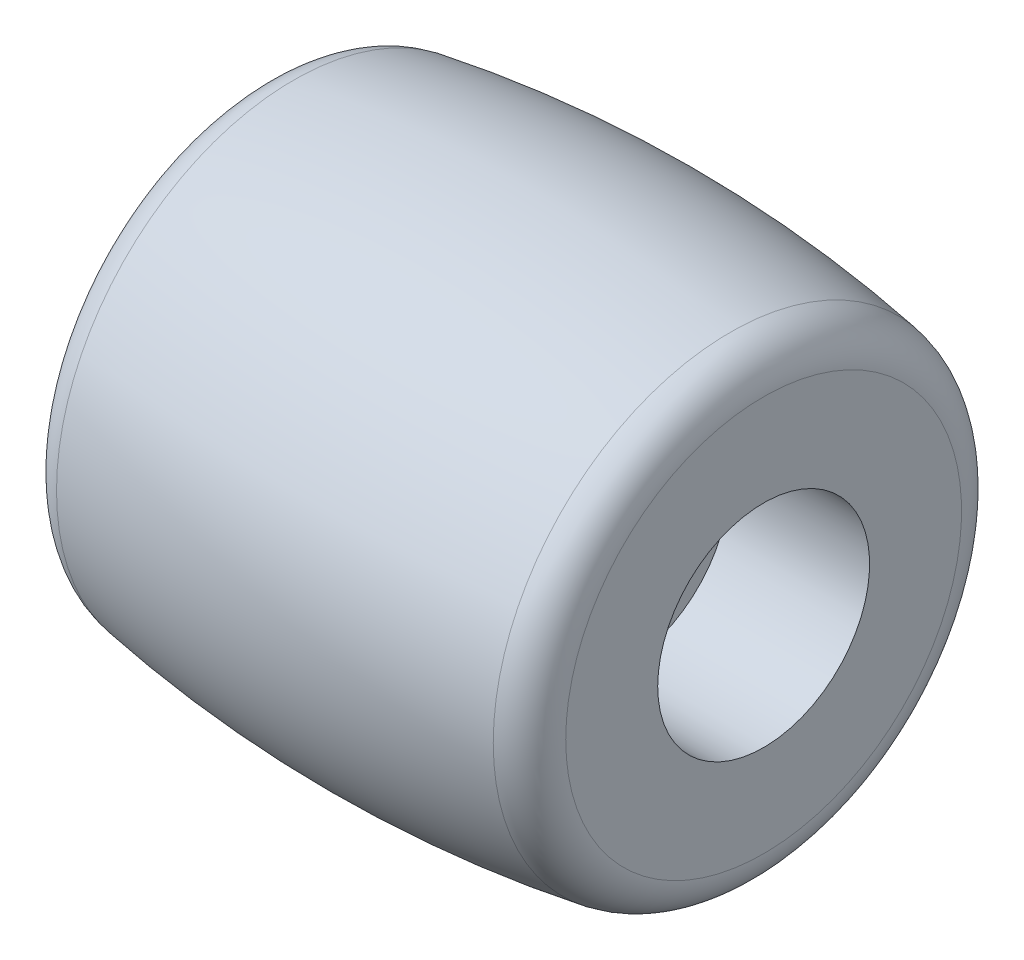
SolidWorks part; units mm, degrees
material "天然ｺﾞﾑ"
ref_plane "正面" through (0, 0, 0) normal (0, 0, 1) x (1, 0, 0)
ref_plane "平面" through (0, 0, 0) normal (0, 1, 0) x (1, 0, 0)
ref_plane "右側面" through (0, 0, 0) normal (1, 0, 0) x (0, 0, -1)
sketch "ｽｹｯﾁ1" plane through (0, 0, 0) normal (0, 0, 1) x (1, 0, 0)
  line L0 (0, 0) -> (12131.0927, 0) construction
  line L1 (4.2, 2.5) -> (-4.2, 2.5)
  line L2 (-4.2, 2.5) -> (-4.2, 4)
  line L3 (-4.2, 4) -> (-9.5, 4)
  line L4 (-9.5, 4) -> (-9.5, 8.7288)
  line L5 (4.2, 2.5) -> (4.2, 4)
  line L6 (4.2, 4) -> (9.5, 4)
  line L7 (9.5, 4) -> (9.5, 8.7288)
  line L8 (0, 0) -> (0, 9.625) construction
  arc A0 (-9.5, 8.7288) -> (9.5, 8.7288) centre (0, -41.175) cw
  point P6 (0, 2.5)
  dimension "D3" = 50.8
  dimension "D1" = 19
  dimension "D2" = 19.25
  dimension "D4" = 8
  dimension "D5" = 5
  dimension "D6" = 5.3
revolve "回転1" add sketch "ｽｹｯﾁ1" angle 360 about L0
fillet "ﾌｨﾚｯﾄ1" radius 1.5 2 edges at (9.5, 0, 8.7288) (-9.5, 0, 8.7288)
